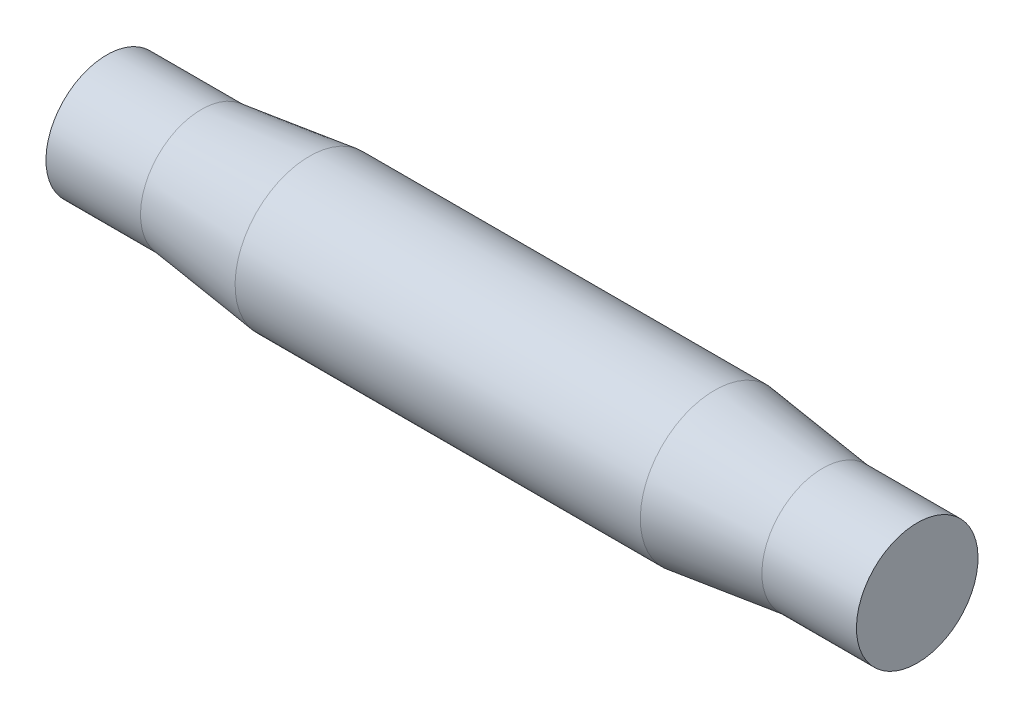
SolidWorks part; units mm, degrees
ref_plane "Plan de face" through (0, 0, 0) normal (0, 0, 1) x (1, 0, 0)
ref_plane "Plan de dessus" through (0, 0, 0) normal (0, 1, 0) x (1, 0, 0)
ref_plane "Plan de droite" through (0, 0, 0) normal (1, 0, 0) x (0, 0, -1)
sketch "Esquisse1" plane through (0, 0, 0) normal (0, 0, 1) x (1, 0, 0)
  line L0 (-30, 0) -> (30, 0)
  line L1 (30, 0) -> (30, 4.5)
  line L2 (30, 4.5) -> (23, 4.5)
  line L3 (23, 4.5) -> (15, 5.5)
  line L4 (15, 5.5) -> (-15, 5.5)
  line L6 (-30, 0) -> (-30, 4.5)
  line L7 (-30, 4.5) -> (-23, 4.5)
  line L8 (-23, 4.5) -> (-15, 5.5)
  dimension "D1" = 4.5
  dimension "D5" = 7
revolve "Révolution1" add sketch "Esquisse1" angle 360 about L0
